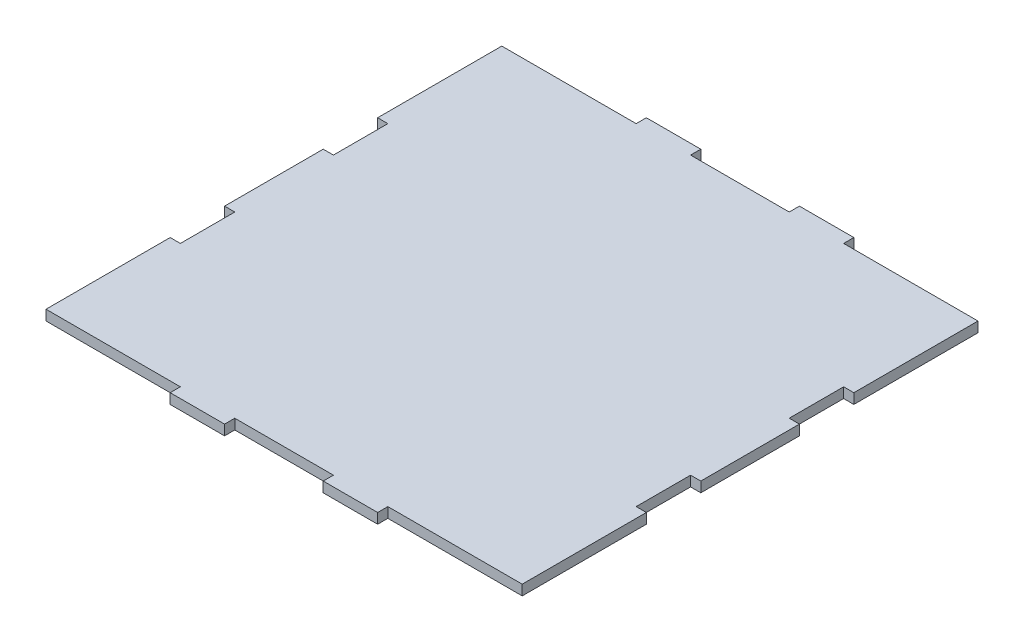
SolidWorks part; units mm, degrees
ref_plane "Front Plane" through (0, 0, 0) normal (0, 0, 1) x (1, 0, 0)
ref_plane "Top Plane" through (0, 0, 0) normal (0, 1, 0) x (1, 0, 0)
ref_plane "Right Plane" through (0, 0, 0) normal (1, 0, 0) x (0, 0, -1)
sketch "Sketch1" plane through (0, 0, 0) normal (0, 1, 0) x (1, 0, 0)
  line L1 (-70, -70) -> (70, -70)
  line L2 (-70, -70) -> (-70, 70)
  line L3 (-70, 70) -> (70, 70)
  line L4 (70, -70) -> (70, 70)
  line L5 (-70, -70) -> (70, 70) construction
  line L6 (-70, 70) -> (70, -70) construction
  point P0 (0, 0)
  dimension "D1" = 140
extrude "Boss-Extrude1" add sketch "Sketch1" along normal blind 3
sketch "Sketch2" plane through (0, 3, 0) normal (0, 1, 0) x (1, 0, 0)
  line L0 (-70, 67) -> (-30.5, 67)
  line L1 (-70, 70) -> (-70, -70) construction
  line L2 (-30.5, 67) -> (-30.5, 70)
  line L3 (70, 70) -> (-70, 70) construction
  line L4 (-30.5, 70) -> (-70, 70)
  line L5 (-70, 70) -> (-70, 67)
  line L6 (-1.65, 0) -> (1.65, 0) construction
  line L7 (-30.5, -70) -> (-70, -70)
  line L8 (-30.5, -67) -> (-30.5, -70)
  line L9 (-70, -67) -> (-30.5, -67)
  line L10 (-70, -70) -> (-70, -67)
  line L11 (0, -1.65) -> (0, 1.65) construction
  line L12 (30.5, -67) -> (30.5, -70)
  line L13 (70, -67) -> (30.5, -67)
  line L14 (70, -70) -> (70, -67)
  line L15 (30.5, -70) -> (70, -70)
  line L16 (30.5, 70) -> (70, 70)
  line L17 (30.5, 67) -> (30.5, 70)
  line L18 (70, 67) -> (30.5, 67)
  line L19 (70, 70) -> (70, 67)
  line L20 (-14.5, 70) -> (-14.5, 67)
  line L21 (-14.5, 67) -> (14.5, 67)
  line L22 (14.5, 67) -> (14.5, 70)
  line L23 (14.5, 70) -> (-14.5, 70)
  line L24 (14.5, -67) -> (14.5, -70)
  line L25 (-14.5, -67) -> (14.5, -67)
  line L26 (-14.5, -70) -> (-14.5, -67)
  line L27 (14.5, -70) -> (-14.5, -70)
  dimension "D1" = 39.5
  dimension "D2" = 3
  dimension "D3" = 3
  dimension "D4" = 29
  dimension "D5" = 55.5
extrude "Cut-Extrude2" cut sketch "Sketch2" against normal blind 3
sketch "Sketch4" plane through (0, 3, 0) normal (0, 1, 0) x (1, 0, 0)
  line L0 (-70, 30.5) -> (-67, 30.5)
  line L1 (-70, 67) -> (-70, -67) construction
  line L2 (-67, 30.5) -> (-67, 14.5)
  line L3 (-67, 14.5) -> (-70, 14.5)
  line L4 (-70, 14.5) -> (-70, 30.5)
  line L5 (-70, 67) -> (-30.5, 67) construction
  line L6 (-1.65, 0) -> (1.65, 0) construction
  line L7 (-67, -14.5) -> (-70, -14.5)
  line L8 (-67, -30.5) -> (-67, -14.5)
  line L9 (-70, -30.5) -> (-67, -30.5)
  line L10 (-70, -14.5) -> (-70, -30.5)
  line L11 (0, -1.65) -> (0, 1.65) construction
  line L12 (67, 14.5) -> (70, 14.5)
  line L13 (67, 30.5) -> (67, 14.5)
  line L14 (70, 30.5) -> (67, 30.5)
  line L15 (70, 14.5) -> (70, 30.5)
  line L16 (67, -30.5) -> (67, -14.5)
  line L17 (70, -30.5) -> (67, -30.5)
  line L18 (70, -14.5) -> (70, -30.5)
  line L19 (67, -14.5) -> (70, -14.5)
  dimension "D1" = 16
  dimension "D2" = 3
  dimension "D3" = 36.5
extrude "Cut-Extrude3" cut sketch "Sketch4" against normal blind 3
